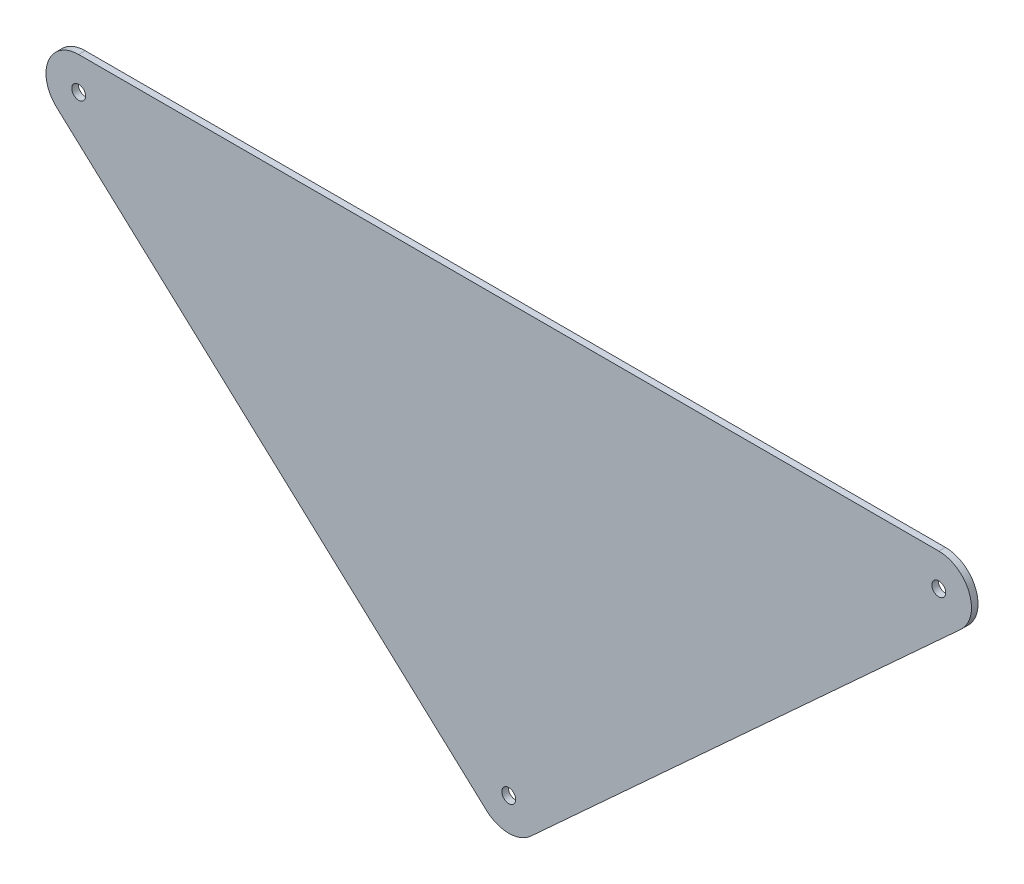
SolidWorks part; units mm, degrees
ref_plane "前视基准面" through (0, 0, 0) normal (0, 0, 1) x (1, 0, 0)
ref_plane "上视基准面" through (0, 0, 0) normal (0, 1, 0) x (1, 0, 0)
ref_plane "右视基准面" through (0, 0, 0) normal (1, 0, 0) x (0, 0, -1)
sketch "草图1" plane through (0, 0, 0) normal (0, 0, 1) x (1, 0, 0)
  line L0 (52.621, 26) -> (-52.621, 26) construction
  line L1 (2.7024, -29.1674) -> (55.3234, 19.0509) construction
  line L2 (-55.3234, 19.0509) -> (-2.7024, -29.1674) construction
  line L3 (52.621, 26) -> (-52.621, 26)
  line L4 (2.7024, -29.1674) -> (55.3234, 19.0509)
  line L5 (-55.3234, 19.0509) -> (-2.7024, -29.1674)
  arc A0 (-52.621, 26) -> (-55.3234, 19.0509) centre (-52.621, 22) ccw construction
  arc A1 (55.3234, 19.0509) -> (52.621, 26) centre (52.621, 22) ccw construction
  arc A2 (-2.7024, -29.1674) -> (2.7024, -29.1674) centre (0, -26.2183) ccw construction
  circle A3 centre (-52.621, 22) radius 0.85 construction
  circle A4 centre (52.621, 22) radius 0.85 construction
  circle A5 centre (0, -26.2183) radius 0.85 construction
  arc A6 (-52.621, 26) -> (-55.3234, 19.0509) centre (-52.621, 22) ccw
  arc A7 (55.3234, 19.0509) -> (52.621, 26) centre (52.621, 22) ccw
  arc A8 (-2.7024, -29.1674) -> (2.7024, -29.1674) centre (0, -26.2183) ccw
  circle A9 centre (-52.621, 22) radius 0.85
  circle A10 centre (52.621, 22) radius 0.85
  circle A11 centre (0, -26.2183) radius 0.85
extrude "凸台-拉伸1" add sketch "草图1" along normal blind 0.8
